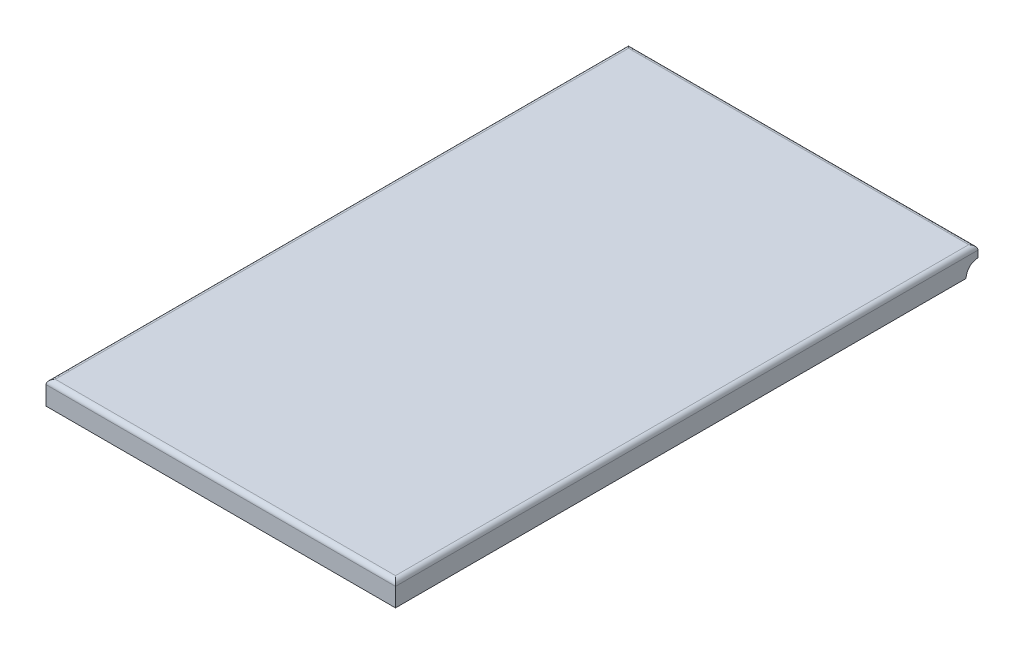
SolidWorks part; units mm, degrees
ref_plane "Front Plane" through (0, 0, 0) normal (0, 0, 1) x (1, 0, 0)
ref_plane "Top Plane" through (0, 0, 0) normal (0, 1, 0) x (1, 0, 0)
ref_plane "Right Plane" through (0, 0, 0) normal (1, 0, 0) x (0, 0, -1)
sketch "Sketch1" plane through (0, 0, 0) normal (0, 0, 1) x (1, 0, 0)
  line L1 (0, 0) -> (150, 0)
  line L2 (0, 0) -> (0, 10)
  line L3 (0, 10) -> (150, 10)
  line L4 (150, 0) -> (150, 10)
  dimension "D1" = 150
  dimension "D2" = 10
extrude "Boss-Extrude1" add sketch "Sketch1" along normal blind 250
fillet "Fillet1" radius 2 4 edges at (75, 10, 0) (0, 10, 125) (150, 10, 125) (75, 10, 250)
sketch "Sketch2" plane through (150, 0, 0) normal (1, 0, 0) x (0, 0, -1)
  circle A0 centre (0, 0) radius 5.1
  dimension "D1" = 10.2
extrude "Cut-Extrude1" cut sketch "Sketch2" against normal blind 30.1
sketch "Sketch3" plane through (119.9, 0, 0) normal (1, 0, 0) x (0, 0, -1)
  circle A0 centre (0, 0) radius 5
  dimension "D1" = 10
extrude "Boss-Extrude2" add sketch "Sketch3" against normal blind 29.85
sketch "Sketch4" plane through (90.05, 0, 0) normal (-1, 0, 0) x (0, 0, 1)
  circle A0 centre (0, 0) radius 5.1
  dimension "D1" = 10.2
extrude "Cut-Extrude2" cut sketch "Sketch4" along normal blind 30.1
sketch "Sketch5" plane through (59.95, 0, 0) normal (1, 0, 0) x (0, 0, -1)
  circle A0 centre (0, 0) radius 5
  dimension "D1" = 10
extrude "Boss-Extrude3" add sketch "Sketch5" against normal blind 29.85
sketch "Sketch6" plane through (30.1, 0, 0) normal (-1, 0, 0) x (0, 0, 1)
  circle A0 centre (0, 0) radius 5.1
  dimension "D1" = 10.2
extrude "Cut-Extrude3" cut sketch "Sketch6" along normal blind 30.1 contours A0
sketch "Sketch7" plane through (119.9, 0, 0) normal (1, 0, 0) x (0, 0, -1)
  circle A0 centre (0, 0) radius 0.875
  dimension "D1" = 1.75
extrude "Cut-Extrude4" cut sketch "Sketch7" against normal blind 90.1
